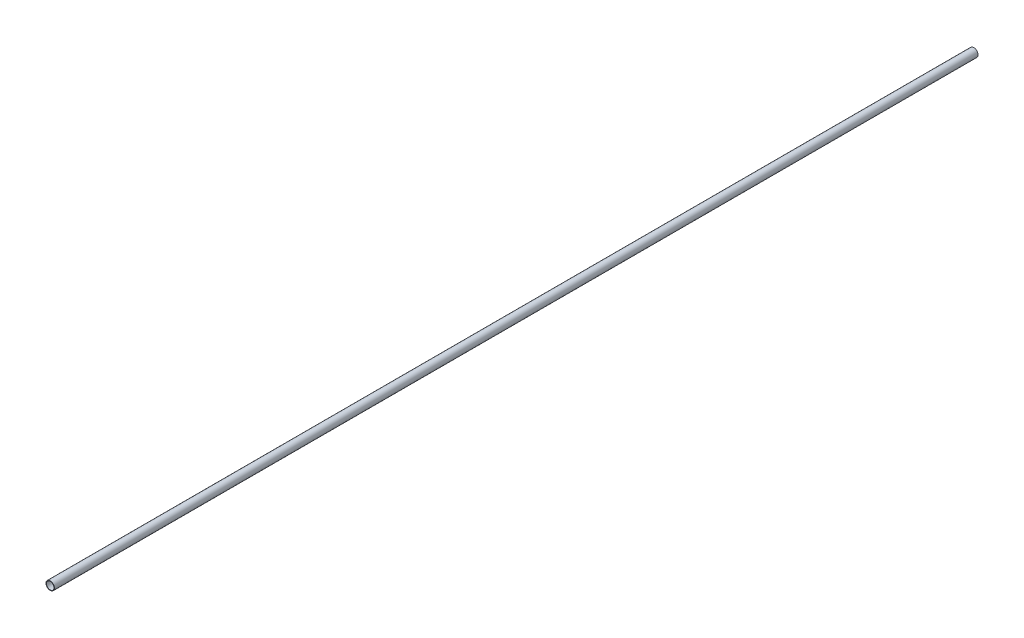
SolidWorks part; units mm, degrees
ref_plane "Front Plane" through (0, 0, 0) normal (0, 0, 1) x (1, 0, 0)
ref_plane "Top Plane" through (0, 0, 0) normal (0, 1, 0) x (1, 0, 0)
ref_plane "Right Plane" through (0, 0, 0) normal (1, 0, 0) x (0, 0, -1)
sketch "Sketch1" plane through (0, 0, 0) normal (0, 0, 1) x (1, 0, 0)
  circle A0 centre (0, 0) radius 11.1
  circle A1 centre (0, 0) radius 9.95
  dimension "D1" = 22.2
  dimension "D2" = 19.9
extrude "Boss-Extrude1" add sketch "Sketch1" along normal blind 2440
